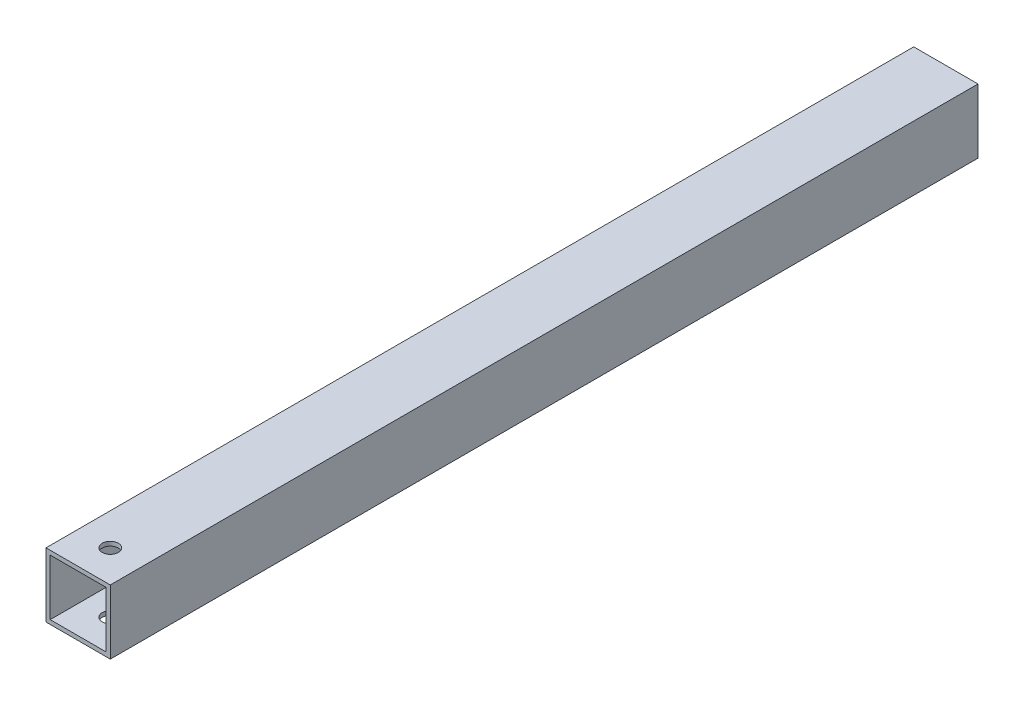
SolidWorks part; units mm, degrees
material "6061 Alloy"
ref_plane "Front Plane" through (0, 0, 0) normal (0, 0, 1) x (1, 0, 0)
ref_plane "Top Plane" through (0, 0, 0) normal (0, 1, 0) x (1, 0, 0)
ref_plane "Right Plane" through (0, 0, 0) normal (1, 0, 0) x (0, 0, -1)
sketch "Sketch1" plane through (0, 0, 0) normal (0, 0, 1) x (1, 0, 0)
  line L1 (-83.2356, -51.039) -> (-57.8356, -51.039)
  line L2 (-83.2356, -51.039) -> (-83.2356, -25.639)
  line L3 (-83.2356, -25.639) -> (-57.8356, -25.639)
  line L4 (-57.8356, -51.039) -> (-57.8356, -25.639)
  dimension "D1" = 25.4
  dimension "D2" = 25.4
extrude "Boss-Extrude1" add sketch "Sketch1" along normal blind 342.9
sketch "Sketch2" plane through (0, 0, 342.9) normal (0, 0, 1) x (1, 0, 0)
  line L0 (-83.2356, -25.639) -> (-83.2356, -51.039) construction
  line L1 (-81.5846, -27.29) -> (-59.4866, -27.29)
  line L2 (-81.5846, -27.29) -> (-81.5846, -49.388)
  line L3 (-81.5846, -49.388) -> (-59.4866, -49.388)
  line L4 (-59.4866, -27.29) -> (-59.4866, -49.388)
  line L5 (-57.8356, -25.639) -> (-83.2356, -25.639) construction
  line L6 (-57.8356, -51.039) -> (-57.8356, -25.639) construction
  line L7 (-83.2356, -51.039) -> (-57.8356, -51.039) construction
  dimension "D1" = 1.651
  dimension "D2" = 1.651
  dimension "D3" = 1.651
  dimension "D4" = 1.651
extrude "Cut-Extrude1" cut sketch "Sketch2" against normal through all
sketch "Sketch4" plane through (0, -51.039, 0) normal (0, -1, 0) x (1, 0, 0)
  line L0 (-83.2356, 342.9) -> (-57.8356, 342.9) construction
  line L1 (-57.8356, 342.9) -> (-57.8356, 0) construction
  circle A0 centre (-70.5356, 330.2) radius 3.175
  dimension "D1" = 6.35
  dimension "D2" = 12.7
  dimension "D3" = 12.7
extrude "Cut-Extrude3" cut sketch "Sketch4" against normal through all
